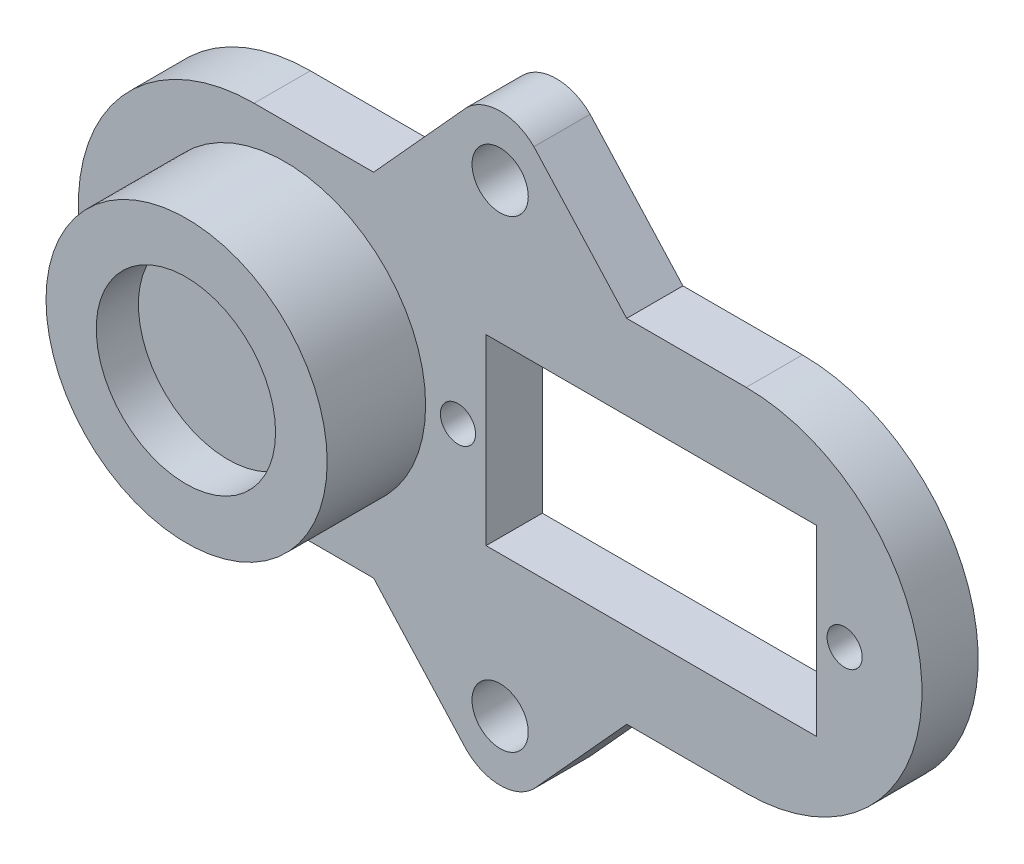
SolidWorks part; units mm, degrees
ref_plane "Front" through (0, 0, 0) normal (0, 0, 1) x (1, 0, 0)
ref_plane "Top" through (0, 0, 0) normal (0, 1, 0) x (1, 0, 0)
ref_plane "Right" through (0, 0, 0) normal (1, 0, 0) x (0, 0, -1)
sketch "Sketch1" plane through (0, 0, 0) normal (0, 0, 1) x (1, 0, 0)
  line L0 (-9, 12.5) -> (-2.401, 19.7724)
  line L1 (-17.5, 12.5) -> (-9, 12.5)
  line L5 (2.401, 19.7724) -> (9, 12.5)
  line L6 (9, 12.5) -> (17.5, 12.5)
  line L7 (-52.4135, 0) -> (76.2531, 0) construction
  line L12 (9, -12.5) -> (17.5, -12.5)
  line L13 (2.401, -19.7724) -> (9, -12.5)
  line L14 (-17.5, -12.5) -> (-9, -12.5)
  line L15 (-9, -12.5) -> (-2.401, -19.7724)
  line L19 (0, 44.7347) -> (0, -34.4115) construction
  line L24 (-1, 6.5) -> (22.5, 6.5)
  line L25 (-1, 6.5) -> (-1, -6.5)
  line L26 (-1, -6.5) -> (22.5, -6.5)
  line L27 (22.5, 6.5) -> (22.5, -6.5)
  circle A2 centre (0, 16.5) radius 2
  arc A4 (-2.401, 19.7724) -> (2.401, 19.7724) centre (0, 17.3714) cw
  arc A5 (-2.401, -19.7724) -> (2.401, -19.7724) centre (0, -17.3714) ccw
  circle A6 centre (0, -16.5) radius 2
  arc A11 (17.5, -12.5) -> (17.5, 12.5) centre (17.5, 0) ccw
  arc A12 (-17.5, 12.5) -> (-17.5, -12.5) centre (-17.5, 0) ccw
  circle A13 centre (-3, 0) radius 1.25
  circle A14 centre (24.5, 0) radius 1.25
  point P32 (-1, 0)
  dimension "D3" = 17.5
  dimension "D4" = 17.5
  dimension "D9" = 4
  dimension "D10" = 13
  dimension "D5" = 2.5
  dimension "D6" = 27.5
  dimension "D2" = 12.5
  dimension "D1" = 2.5
  dimension "D7" = 3
  dimension "D8" = 23.5
  dimension "D11" = 2
extrude "Boss-Extrude1" add sketch "Sketch1" along normal blind 4
sketch "Sketch3" plane through (0, 0, 4) normal (0, 0, 1) x (1, 0, 0)
  circle A0 centre (-15.3, 0) radius 10
  dimension "D1" = 20
  dimension "D2" = 15.3
extrude "Boss-Extrude2" add sketch "Sketch3" along normal blind 7
sketch "Sketch4" plane through (0, 0, 11) normal (0, 0, 1) x (1, 0, 0)
  circle A0 centre (-15.35, 0) radius 6.3775
extrude "Cut-Extrude1" cut sketch "Sketch4" against normal blind 3
